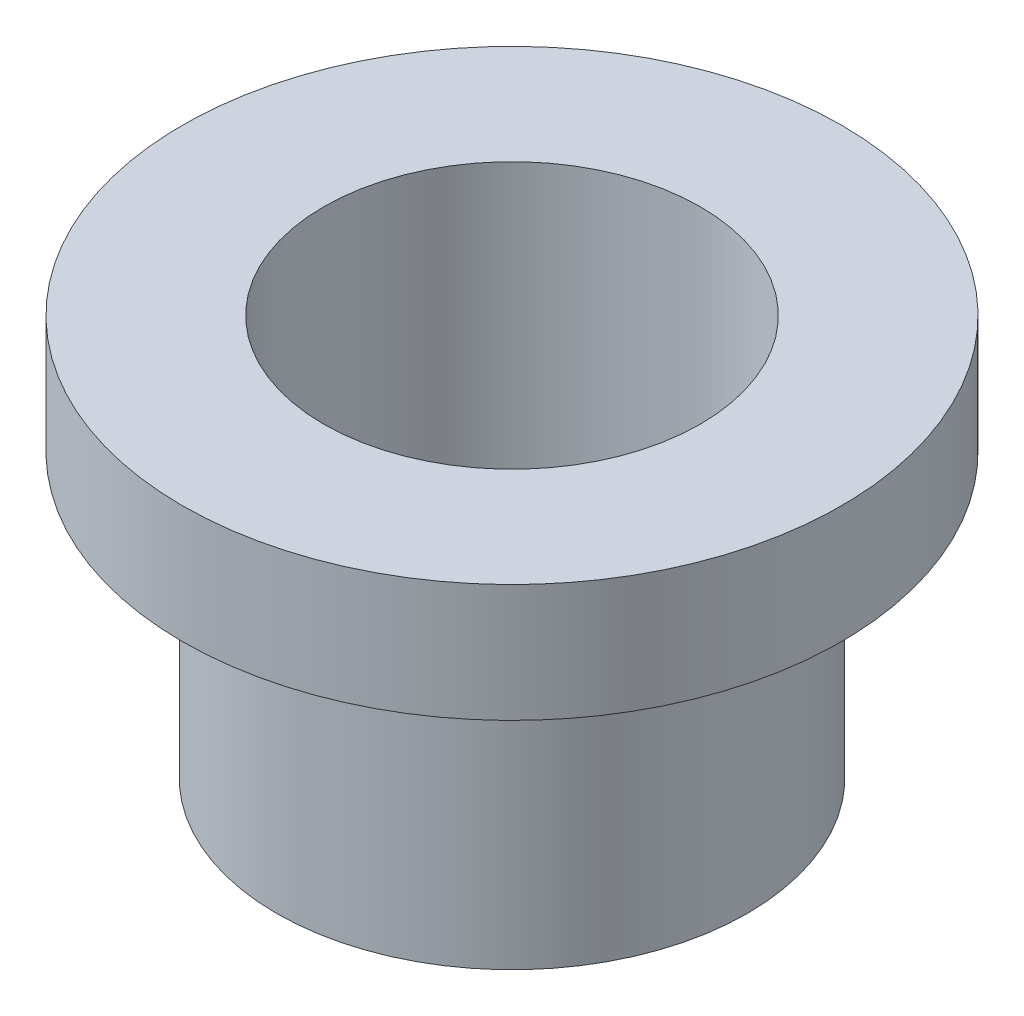
SolidWorks part; units mm, degrees
ref_plane "Front Plane" through (0, 0, 0) normal (0, 0, 1) x (1, 0, 0)
ref_plane "Top Plane" through (0, 0, 0) normal (0, 1, 0) x (1, 0, 0)
ref_plane "Right Plane" through (0, 0, 0) normal (1, 0, 0) x (0, 0, -1)
sketch "Sketch1" plane through (0, 0, 0) normal (0, 0, 1) x (1, 0, 0)
  line L0 (0, 13.2961) -> (0, -13.2961) construction
  line L1 (4, 2.5) -> (7, 2.5)
  line L2 (7, 2.5) -> (7, 0)
  line L3 (7, 0) -> (5, 0)
  line L4 (5, 0) -> (5, -6)
  line L5 (5, -6) -> (4, -6)
  line L6 (4, -6) -> (4, 2.5)
  line L7 (5, 0) -> (0, 0) construction
  point P4 (0, 0)
  dimension "ID" = 8
  dimension "Flange Thickness" = 2.5
  dimension "Major OD" = 14
  dimension "Minor OD" = 10
  dimension "Length" = 6
revolve "Revolve1" add sketch "Sketch1" angle 360 about L0
equation "\"ID\"=4"
